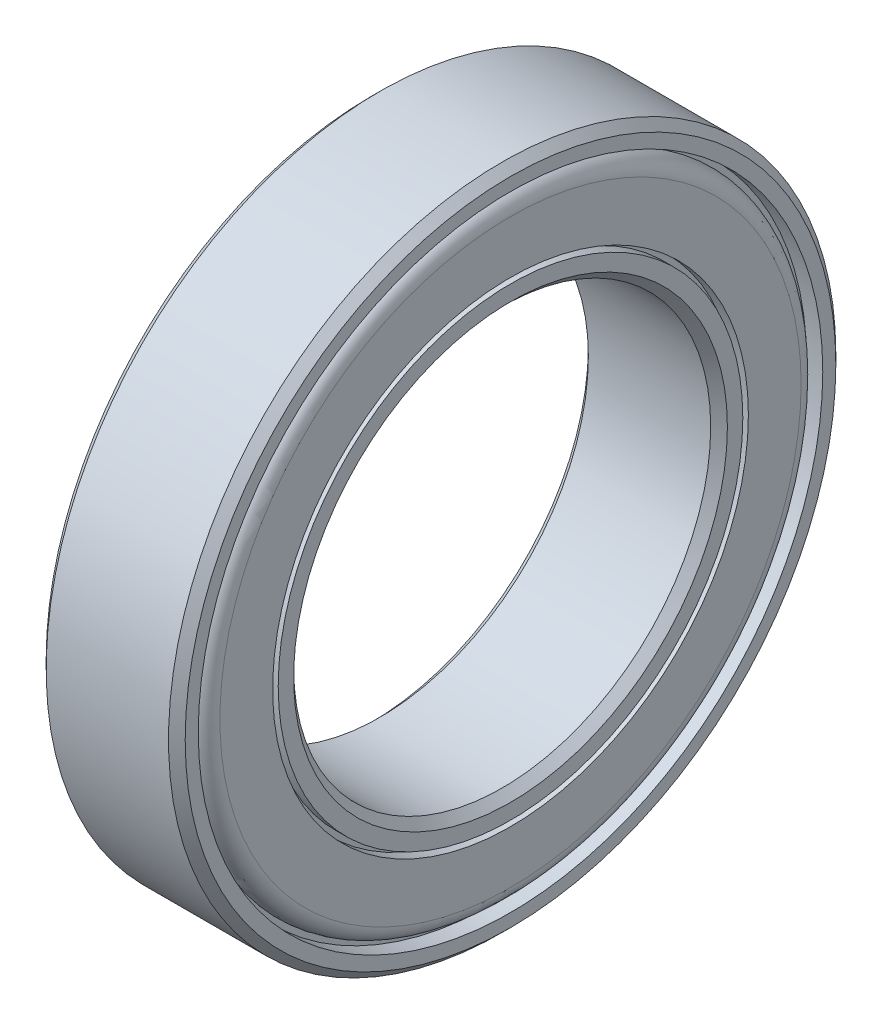
SolidWorks part; units mm, degrees
ref_plane "Front Plane" through (0, 0, 0) normal (0, 0, 1) x (1, 0, 0)
ref_plane "Top Plane" through (0, 0, 0) normal (0, 1, 0) x (1, 0, 0)
ref_plane "Right Plane" through (0, 0, 0) normal (1, 0, 0) x (0, 0, -1)
sketch "Sketch1" plane through (0, 0, 0) normal (1, 0, 0) x (0, 0, -1)
  circle A0 centre (0, 0) radius 12
  circle A1 centre (0, 0) radius 7.5
  dimension "D1" = 15
  dimension "D2" = 24
extrude "Boss-Extrude1" add sketch "Sketch1" along normal mid plane 5
chamfer "Chamfer1" distance 0.3 angle 45 4 edges at (-2.5, 0, -7.5) (2.5, 0, -7.5) (-2.5, 0, -12) (2.5, 0, -12)
sketch "Sketch2" plane through (0, 0, 0) normal (0, 0, 1) x (1, 0, 0)
  line L0 (2.9397, 11.2301) -> (1.9208, 11.2301)
  line L1 (1.9208, 11.2301) -> (1.9208, 11.0301)
  line L3 (2.5, -11.7) -> (2.5, 11.7) construction
  line L4 (2.5, 10.4509) -> (2.5, 8.5545)
  line L5 (2.5, 8.5545) -> (2.0848, 8.5545)
  line L6 (2.0848, 8.5545) -> (2.0848, 8.3545)
  line L7 (2.0848, 8.3545) -> (2.9397, 8.3545)
  line L8 (2.9397, 8.3545) -> (2.9397, 11.2301)
  line L9 (1.9208, 10.4509) -> (1.9208, 11.0301) construction
  arc A0 (2.5, 10.4509) -> (1.9208, 11.0301) centre (1.9208, 10.4509) ccw
  dimension "D1" = 0.2
ref_axis "Axis1" through (3.2117, 0, 0) along (-1, 0, 0)
revolve "Cut-Revolve1" cut sketch "Sketch2" angle 360 about axis through (3.2117, 0, 0) along (-1, 0, 0)
mirror "Mirror1" about plane through (0, 0, 0) normal (1, 0, 0) of "Cut-Revolve1"
